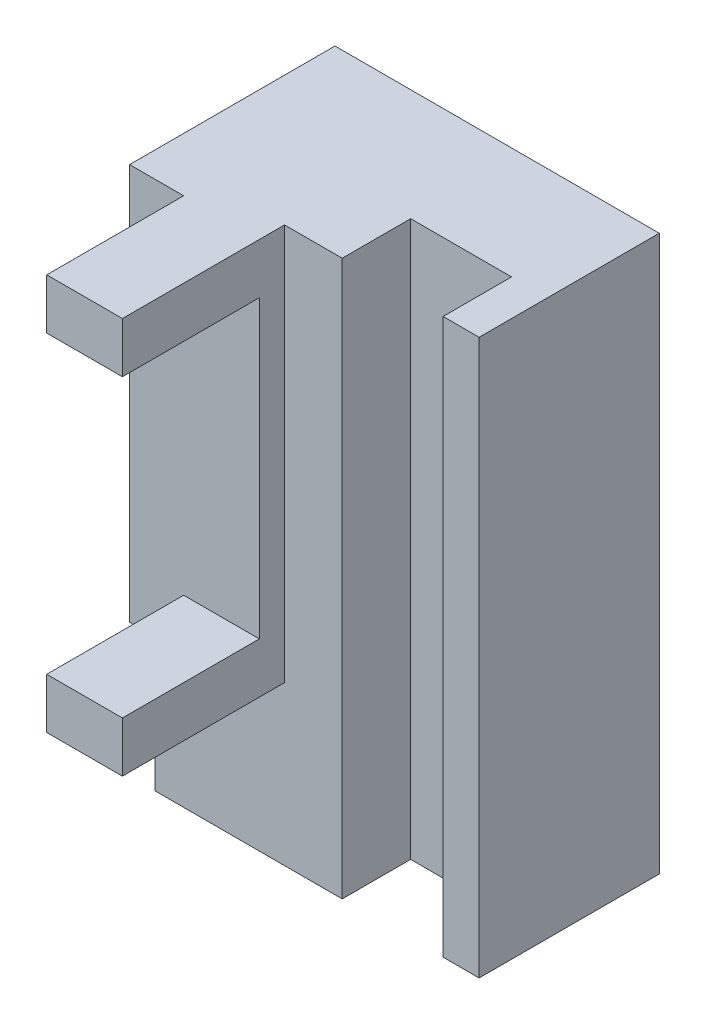
SolidWorks part; units mm, degrees
ref_plane "Front Plane" through (0, 0, 0) normal (0, 0, 1) x (1, 0, 0)
ref_plane "Top Plane" through (0, 0, 0) normal (0, 1, 0) x (1, 0, 0)
ref_plane "Right Plane" through (0, 0, 0) normal (1, 0, 0) x (0, 0, -1)
sketch "Sketch4" plane through (0, 0, 0) normal (0, 0, 1) x (1, 0, 0)
  line L1 (-28.7781, 55.5758) -> (16.2219, 55.5758)
  line L2 (-28.7781, 55.5758) -> (-28.7781, -21.4242)
  line L3 (-28.7781, -21.4242) -> (16.2219, -21.4242)
  line L4 (16.2219, 55.5758) -> (16.2219, -21.4242)
  dimension "D1" = 77
  dimension "D2" = 45
extrude "Boss-Extrude1" add sketch "Sketch4" along normal blind 25
sketch "Sketch6" plane through (0, -21.4242, 0) normal (0, -1, 0) x (1, 0, 0)
  line L0 (-28.7781, 25) -> (16.2219, 25) construction
  line L1 (-2.7781, 25) -> (11.2219, 25)
  line L2 (-2.7781, 25) -> (-2.7781, 15.5)
  line L3 (-2.7781, 15.5) -> (11.2219, 15.5)
  line L4 (11.2219, 25) -> (11.2219, 15.5)
  line L5 (16.2219, 25) -> (16.2219, 0) construction
  dimension "D1" = 9.5
  dimension "D2" = 14
  dimension "D3" = 5
extrude "Cut-Extrude1" cut sketch "Sketch6" against normal through all
sketch "Sketch7" plane through (0, 0, 25) normal (0, 0, 1) x (1, 0, 0)
  line L0 (-2.7781, 55.5758) -> (-28.7781, 55.5758) construction
  line L1 (-21.2781, 55.5758) -> (-10.7781, 55.5758)
  line L2 (-21.2781, 55.5758) -> (-21.2781, 0.5758)
  line L3 (-21.2781, 0.5758) -> (-10.7781, 0.5758)
  line L4 (-10.7781, 55.5758) -> (-10.7781, 0.5758)
  line L5 (-2.7781, 55.5758) -> (-2.7781, -21.4242) construction
  dimension "D1" = 55
  dimension "D2" = 8
  dimension "D3" = 10.5
extrude "Boss-Extrude2" add sketch "Sketch7" along normal blind 3.5
sketch "Sketch8" plane through (0, 0, 28.5) normal (0, 0, 1) x (1, 0, 0)
  line L0 (-21.2781, 55.5758) -> (-21.2781, 0.5758) construction
  line L1 (-10.7781, 0.5758) -> (-21.2781, 0.5758)
  line L2 (-10.7781, 0.5758) -> (-10.7781, 7.5758)
  line L3 (-10.7781, 7.5758) -> (-21.2781, 7.5758)
  line L4 (-21.2781, 0.5758) -> (-21.2781, 7.5758)
  line L5 (-10.7781, 0.5758) -> (-10.7781, 55.5758) construction
  line L6 (-21.2781, 55.5758) -> (-10.7781, 55.5758)
  line L7 (-21.2781, 55.5758) -> (-21.2781, 48.5758)
  line L8 (-21.2781, 48.5758) -> (-10.7781, 48.5758)
  line L9 (-10.7781, 55.5758) -> (-10.7781, 48.5758)
  dimension "D1" = 7
  dimension "D2" = 7
extrude "Boss-Extrude3" add sketch "Sketch8" along normal blind 19
sketch "Sketch9" plane through (0, 0, 25) normal (0, 0, 1) x (1, 0, 0)
  line L0 (-28.7781, 55.5758) -> (-28.7781, -21.4242) construction
  line L1 (-21.2781, 55.5758) -> (-28.7781, 55.5758)
  line L2 (-21.2781, 55.5758) -> (-21.2781, 0.5758)
  line L3 (-21.2781, 0.5758) -> (-28.7781, 0.5758)
  line L4 (-28.7781, 55.5758) -> (-28.7781, 0.5758)
extrude "Boss-Extrude4" add sketch "Sketch9" along normal blind 3.5
